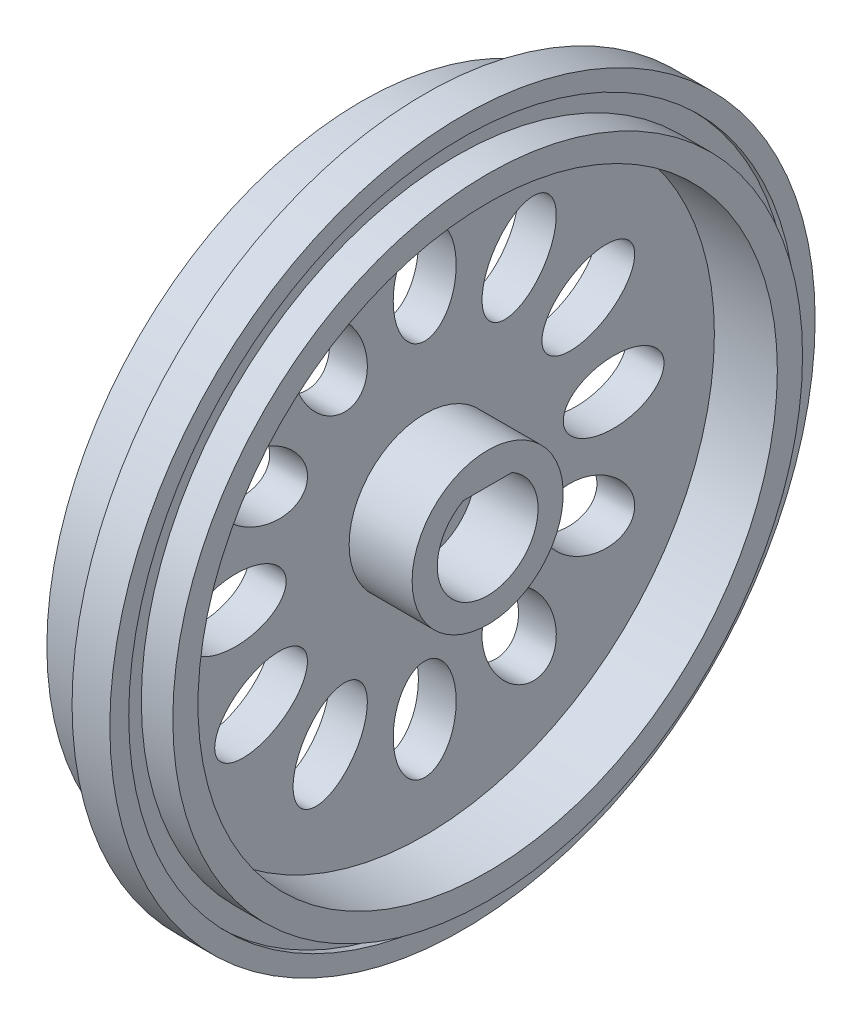
SolidWorks part; units mm, degrees
ref_plane "Front Plane" through (0, 0, 0) normal (0, 0, 1) x (1, 0, 0)
ref_plane "Top Plane" through (0, 0, 0) normal (0, 1, 0) x (1, 0, 0)
ref_plane "Right Plane" through (0, 0, 0) normal (1, 0, 0) x (0, 0, -1)
sketch "Sketch1" plane through (0, 0, 0) normal (0, 1, 0) x (1, 0, 0)
  line L0 (0, 0) -> (7.4746, 0) construction
  line L1 (-5, 25) -> (0.5, 25)
  line L2 (0.5, 25) -> (0.5, 26.5)
  line L3 (0.5, 26.5) -> (0, 26.5)
  line L4 (0, 26.5) -> (0, 28)
  line L5 (0, 28) -> (3, 28)
  line L6 (3, 28) -> (3, 26.5)
  line L7 (3, 26.5) -> (2.5, 26.5)
  line L8 (2.5, 26.5) -> (2.5, 25)
  line L9 (2.5, 25) -> (5, 25)
  line L10 (5, 25) -> (5, 0)
  line L11 (5, 0) -> (-5, 0)
  line L12 (-5, 0) -> (-5, 25)
  line L13 (1.5, 26.1034) -> (1.5, 23.6814) construction
  point P15 (2.75, 26.5)
  dimension "D1" = 3
  dimension "D2" = 28
  dimension "D3" = 1.5
  dimension "D4" = 1.5
  dimension "D5" = 10
  dimension "D6" = 1
  dimension "D7" = 2
  dimension "D8" = 1.5
  dimension "D9" = 3.5
  dimension "D10" = 5
revolve "Revolve1" add sketch "Sketch1" angle 360 about L0
sketch "Sketch2" plane through (5, 0, 0) normal (1, 0, 0) x (0, 0, -1)
  circle A2 centre (0, 0) radius 23
  circle A3 centre (0, 0) radius 23
  dimension "D1" = 2
extrude "Cut-Extrude1" cut sketch "Sketch2" against normal blind 5
sketch "Sketch3" plane through (-5, 0, 0) normal (-1, 0, 0) x (0, 0, 1)
  circle A2 centre (0, 0) radius 23
  circle A3 centre (0, 0) radius 23
  dimension "D1" = 2
extrude "Cut-Extrude2" cut sketch "Sketch3" against normal blind 2 contours A3
sketch "Sketch4" plane through (0, 0, 0) normal (1, 0, 0) x (0, 0, -1)
  circle A0 centre (0, 0) radius 6
  dimension "D1" = 12
extrude "Boss-Extrude2" add sketch "Sketch4" along normal up to surface (5 mm away) up to face at (5, 0, -23)
sketch "Sketch5" plane through (5, 0, 0) normal (1, 0, 0) x (0, 0, -1)
  line L0 (-1.9365, 3.5) -> (1.9365, 3.5)
  arc A0 (-1.9365, 3.5) -> (1.9365, 3.5) centre (0, 0) ccw
  dimension "D1" = 8
  dimension "D2" = 3.5
extrude "Cut-Extrude3" cut sketch "Sketch5" against normal offset from surface (5 mm away) 3 up to face at (-3, 0, 23)
sketch "Sketch6" plane through (-3, 0, 0) normal (-1, 0, 0) x (0, 0, 1)
  circle A0 centre (0, 0) radius 1.5
  dimension "D1" = 3
extrude "Cut-Extrude4" cut sketch "Sketch6" against normal up to surface (3 mm away) up to face at (0, -0.25, 0)
sketch "Sketch7" plane through (0, 0, 0) normal (1, 0, 0) x (0, 0, -1)
  ellipse E0 centre (0, 15) end of major axis (0, 11) minor radius 2.5
  dimension "D1" = 5
  dimension "D2" = 8
  dimension "D3" = 15
extrude "Cut-Extrude5" cut sketch "Sketch7" against normal up to surface (3 mm away) up to face at (-3, 0, 1.5)
pattern_circular "CirPattern1" count 12 over 360 about axis through (4.2426, 0, 0) along (-1, 0, 0) of "Cut-Extrude5"
